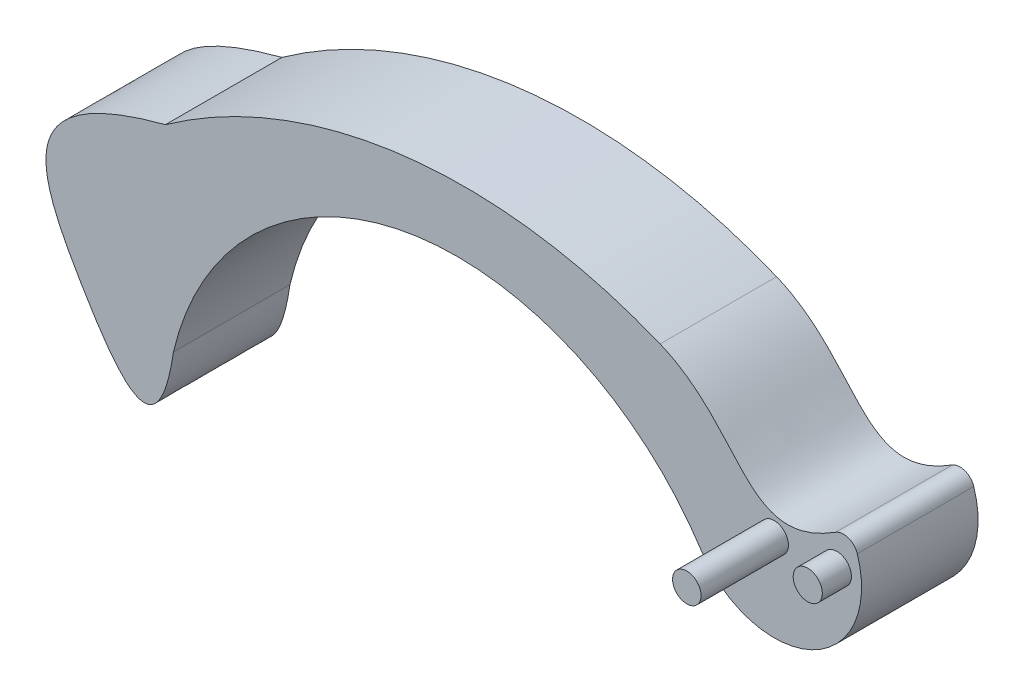
SolidWorks part; units mm, degrees
ref_plane "前视基准面" through (0, 0, 0) normal (0, 0, 1) x (1, 0, 0)
ref_plane "上视基准面" through (0, 0, 0) normal (0, 1, 0) x (1, 0, 0)
ref_plane "右视基准面" through (0, 0, 0) normal (1, 0, 0) x (0, 0, -1)
other "Configuration Table"
sketch "草图1" plane through (0, 0, 0) normal (0, 0, 1) x (1, 0, 0)
  arc A1 (5.2989, 15.2101) -> (-45.6882, -16.3878) centre (-20.5563, -0.0052) cw
  arc A2 (-45.6882, -16.3878) -> (-226.8114, -48.1279) centre (-129.4613, -70.9962) ccw
  arc A3 (-59.7326, 37.8115) -> (-229.5467, 18.1042) centre (-126.8041, -125.7283) ccw
  spline S0 degree 3 poles (5.2989, 15.2101) (-30.4124, -10.923) (-29.6711, 25.4826) (-59.7326, 37.8115) knots 0 0 0 0 1 1 1 1
  spline S1 degree 3 poles (-226.8114, -48.1279) (-232.1711, -84.6853) (-269.7981, -29.1392) (-283.0095, 4.0447) (-229.5467, 18.1042) knots 0 0 0 0 0.380869 1 1 1 1
  dimension "D1" = 100
  dimension "D2" = 30
extrude "凸台-拉伸1" add sketch "草图1" along normal blind 40
fillet "圆角1" radius 5 1 edges at (5.2989, 15.2101, 20)
sketch "草图2" plane through (3.1302, 1.2507, 40) normal (0, 0, 1) x (1, 0, 0)
  circle A0 centre (-2.1635, 0.2476) radius 5
extrude "凸台-拉伸2" add sketch "草图2" along normal blind 10
sketch "草图3" plane through (0, 0, 40) normal (0, 0, 1) x (1, 0, 0)
  circle A0 centre (-20.5563, -0.0052) radius 4.8954
  arc A1 (-45.6882, -16.3878) -> (7.9702, 9.2811) centre (-20.5563, -0.0052) ccw construction
extrude "凸台-拉伸3" add sketch "草图3" along normal blind 30
